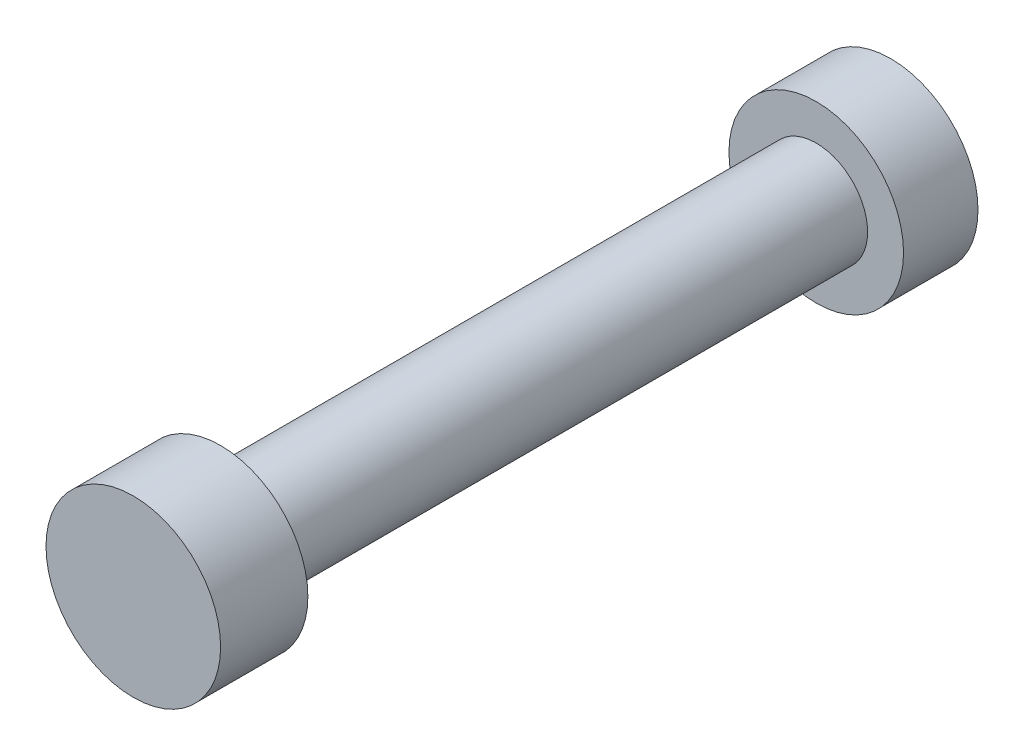
SolidWorks part; units mm, degrees
ref_plane "Front Plane" through (0, 0, 0) normal (0, 0, 1) x (1, 0, 0)
ref_plane "Top Plane" through (0, 0, 0) normal (0, 1, 0) x (1, 0, 0)
ref_plane "Right Plane" through (0, 0, 0) normal (1, 0, 0) x (0, 0, -1)
sketch "Sketch1" plane through (0, 0, 0) normal (0, 0, 1) x (1, 0, 0)
  circle A0 centre (0, 0) radius 2
extrude "M4 shank and grip" add sketch "Sketch1" along normal blind 29.5 from offset 35.5
sketch "Sketch2" plane through (0, 0, 0) normal (0, 0, 1) x (1, 0, 0)
  circle A0 centre (0, 0) radius 3.4
extrude "Head" add sketch "Sketch2" along normal blind 3.4 from offset 61.6
sketch "Sketch3" plane through (0, 0, 0) normal (0, 0, 1) x (1, 0, 0)
  circle A0 centre (0, 0) radius 3.4
extrude "Locknut" add sketch "Sketch3" along normal blind 2.9 from offset 35.5
